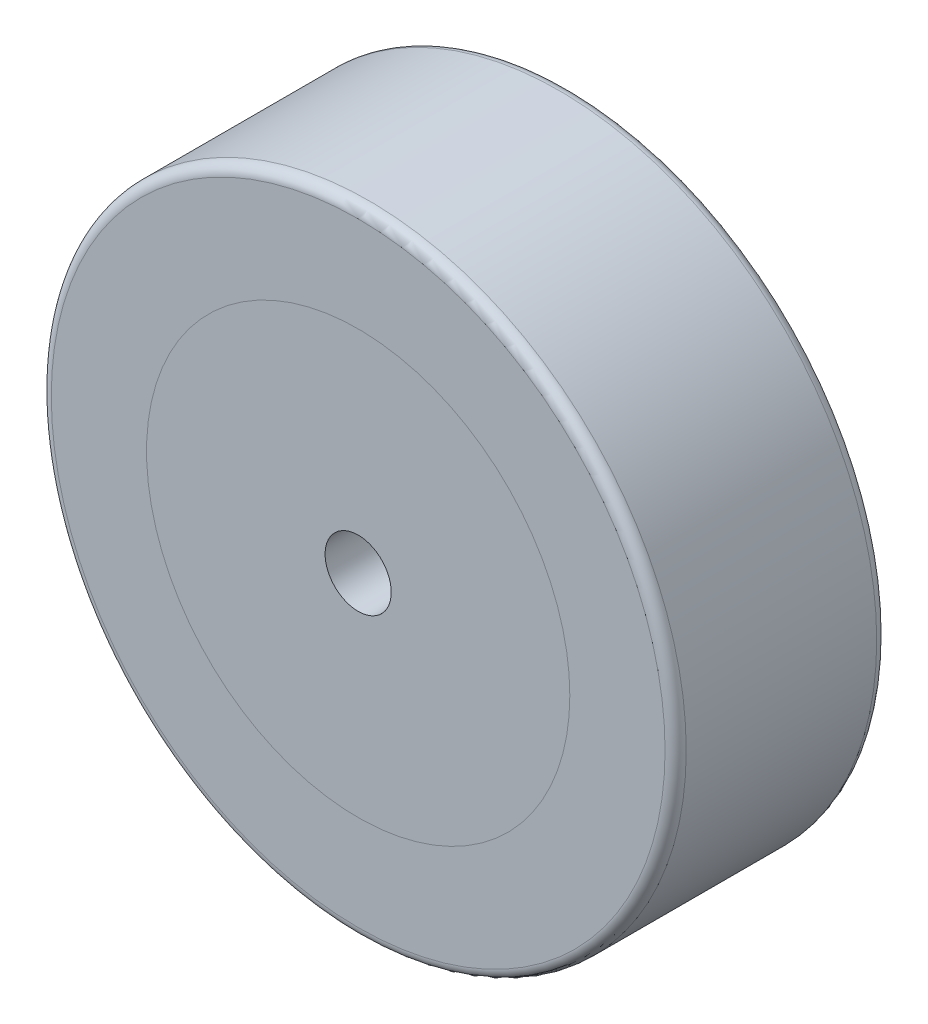
SolidWorks part; units mm, degrees
ref_plane "Front Plane" through (0, 0, 0) normal (0, 0, 1) x (1, 0, 0)
ref_plane "Top Plane" through (0, 0, 0) normal (0, 1, 0) x (1, 0, 0)
ref_plane "Right Plane" through (0, 0, 0) normal (1, 0, 0) x (0, 0, -1)
sketch "Sketch1" plane through (0, 0, 0) normal (0, 0, 1) x (1, 0, 0)
  circle A0 centre (0, 0) radius 50.8
  dimension "D1" = 101.6
extrude "Boss-Extrude1" add sketch "Sketch1" along normal blind 50.8 contours A0
sketch "Sketch2" plane through (0, 0, 0) normal (0, 0, 1) x (1, 0, 0)
  circle A0 centre (0, 0) radius 7.9375
  dimension "D1" = 15.875
extrude "Cut-Extrude1" cut sketch "Sketch2" along normal through all
sketch "Sketch3" plane through (0, 0, 0) normal (0, 0, 1) x (1, 0, 0)
  circle A0 centre (0, 0) radius 50.8 construction
  circle A1 centre (0, 0) radius 50.8
  circle A2 centre (0, 0) radius 76.2
  dimension "D1" = 152.4
extrude "Boss-Extrude2" add sketch "Sketch3" along normal up to surface (50.8 mm away) separate body up to face at (7.9375, 0, 50.8)
fillet "Fillet1" radius 2.54 2 edges at (76.2, 0, 0) (76.2, 0, 50.8)
equation "\"wheel_dia\"= 6in"
equation "\"wheel_width\"= 2in"
equation "\"tire_thickness\"= 1in"
equation "\"hub_dia\"= \"wheel_dia\" - 2 * \"tire_thickness\""
equation "\"D1@Sketch1\"=\"hub_dia\""
equation "\"D1@Boss-Extrude1\"=\"wheel_width\""
equation "\"shaft_dia\"= 5 / 8in"
equation "\"D1@Sketch2\"=\"shaft_dia\""
equation "\"D1@Sketch3\"=\"wheel_dia\""
equation "\"tire_fillet\"=0.1"
equation "\"D1@Fillet1\"=\"tire_fillet\""
